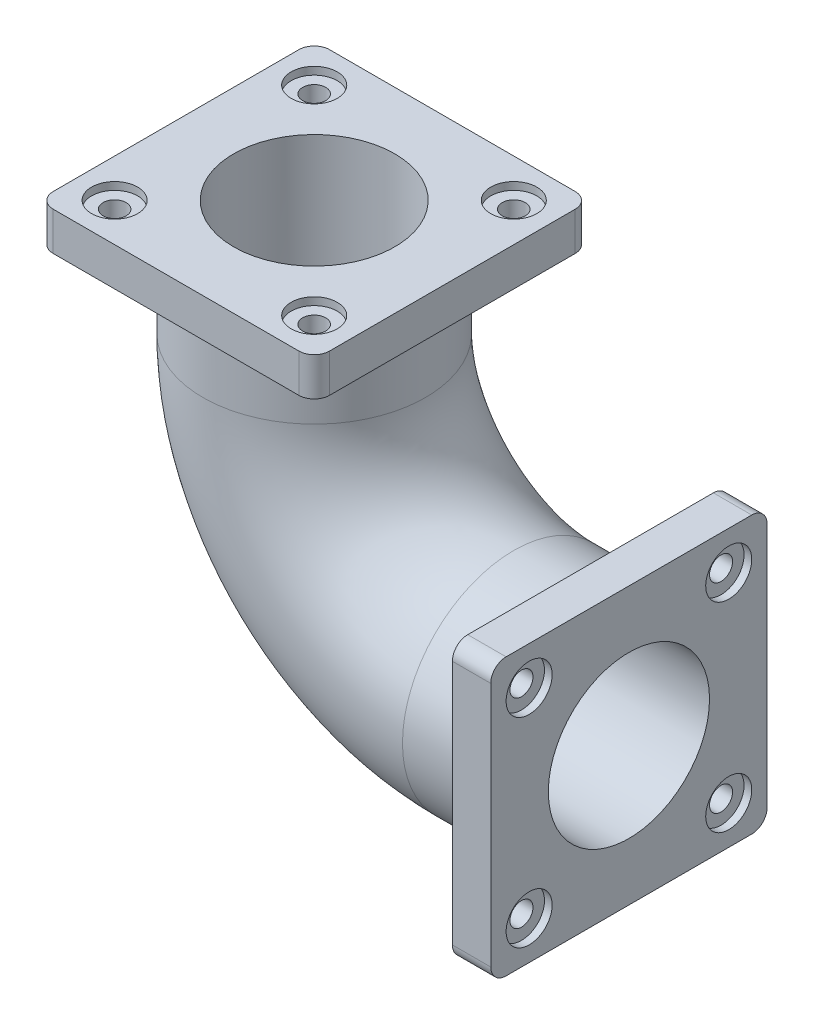
SolidWorks part; units mm, degrees
ref_plane "Front Plane" through (0, 0, 0) normal (0, 0, 1) x (1, 0, 0)
ref_plane "Top Plane" through (0, 0, 0) normal (0, 1, 0) x (1, 0, 0)
ref_plane "Right Plane" through (0, 0, 0) normal (1, 0, 0) x (0, 0, -1)
sketch "Sketch1" plane through (0, 0, 0) normal (0, 0, 1) x (1, 0, 0)
  line L0 (0, 0) -> (-150, 0)
  line L1 (-410, 410) -> (-410, 260)
  arc A0 (-150, 0) -> (-410, 260) centre (-150, 260) cw
  dimension "D2" = 260
  dimension "D1" = 150
  dimension "D3" = 150
sketch "Sketch2" plane through (0, 0, 0) normal (1, 0, 0) x (0, 0, -1)
  circle A0 centre (0, 0) radius 145
  dimension "D1" = 290
sweep "Sweep-Thin1" add profiles "Sketch2" path "Sketch1" parameters "D1"=40
sketch "Sketch3" plane through (0, 0, 0) normal (1, 0, 0) x (0, 0, -1)
  line L1 (180, -180) -> (-180, -180)
  line L2 (180, -180) -> (180, 180)
  line L3 (180, 180) -> (-180, 180)
  line L4 (-180, -180) -> (-180, 180)
  line L5 (180, -180) -> (-180, 180) construction
  line L6 (180, 180) -> (-180, -180) construction
  point P0 (0, 0)
  circle M5 centre (0, 0) radius 145
  dimension "D1" = 360
  dimension "D2" = 360
extrude "Boss-Extrude1" add sketch "Sketch3" against normal blind 50 contours L4 L1 L2 L3 M5
fillet "Fillet1" radius 20 4 edges at (-25, -180, 180) (-25, -180, -180) (-25, 180, -180) (-25, 180, 180)
sketch "Sketch4" plane through (0, 410, 0) normal (0, 1, 0) x (1, 0, 0)
  line L1 (-570, -180) -> (-250, -180)
  line L2 (-590, -160) -> (-590, 160)
  line L3 (-570, 180) -> (-250, 180)
  line L4 (-230, -160) -> (-230, 160)
  line L5 (-590, -180) -> (-230, 180) construction
  line L6 (-590, 180) -> (-230, -180) construction
  arc A0 (-250, -180) -> (-230, -160) centre (-250, -160) ccw
  arc A1 (-570, -180) -> (-590, -160) centre (-570, -160) cw
  arc A2 (-590, 160) -> (-570, 180) centre (-570, 160) cw
  arc A3 (-250, 180) -> (-230, 160) centre (-250, 160) cw
  point P0 (-410, 0)
  point P6 (0, 0)
  point P7 (0, 0)
  circle M6 centre (-410, 0) radius 145
  dimension "D3" = 20
  dimension "D1" = 360
  dimension "D2" = 360
extrude "Boss-Extrude2" add sketch "Sketch4" against normal blind 50 contours A3 L3 A2 L2 A1 L1 A0 L4 M6
sketch "Sketch5" plane through (0, 0, 0) normal (1, 0, 0) x (0, 0, -1)
  line L1 (130, -130) -> (-130, -130) construction
  line L2 (130, -130) -> (130, 130) construction
  line L3 (130, 130) -> (-130, 130) construction
  line L4 (-130, -130) -> (-130, 130) construction
  line L5 (130, -130) -> (-130, 130) construction
  line L6 (130, 130) -> (-130, -130) construction
  circle A0 centre (-130, 130) radius 30
  point P0 (0, 0)
  dimension "D3" = 60
  dimension "D1" = 260
  dimension "D2" = 260
extrude "Cut-Extrude1" cut sketch "Sketch5" against normal blind 10 contours A0
sketch "Sketch6" plane through (0, 0, 0) normal (1, 0, 0) x (0, 0, -1)
  circle A0 centre (-130, 130) radius 15
  dimension "D1" = 30
extrude "Cut-Extrude2" cut sketch "Sketch6" against normal up to next
pattern_circular "CirPattern1" count 4 every 90 about axis through (0, 0, 0) along (1, 0, 0) of "Cut-Extrude1", "Cut-Extrude2"
sketch "Sketch7" plane through (0, 410, 0) normal (0, 1, 0) x (1, 0, 0)
  line L1 (-280, -130) -> (-540, -130) construction
  line L2 (-280, -130) -> (-280, 130) construction
  line L3 (-280, 130) -> (-540, 130) construction
  line L4 (-540, -130) -> (-540, 130) construction
  line L5 (-280, -130) -> (-540, 130) construction
  line L6 (-280, 130) -> (-540, -130) construction
  circle A0 centre (-540, 130) radius 30
  point P0 (-410, 0)
  dimension "D3" = 60
  dimension "D1" = 260
  dimension "D2" = 260
extrude "Cut-Extrude3" cut sketch "Sketch7" against normal blind 10
sketch "Sketch8" plane through (0, 400, 0) normal (0, 1, 0) x (1, 0, 0)
  circle A0 centre (-540, 130) radius 15
  dimension "D1" = 30
extrude "Cut-Extrude4" cut sketch "Sketch8" against normal up to next
pattern_circular "CirPattern2" count 4 every 90 about axis through (-410, 0, 0) along (0, 1, 0) of "Cut-Extrude3", "Cut-Extrude4"
